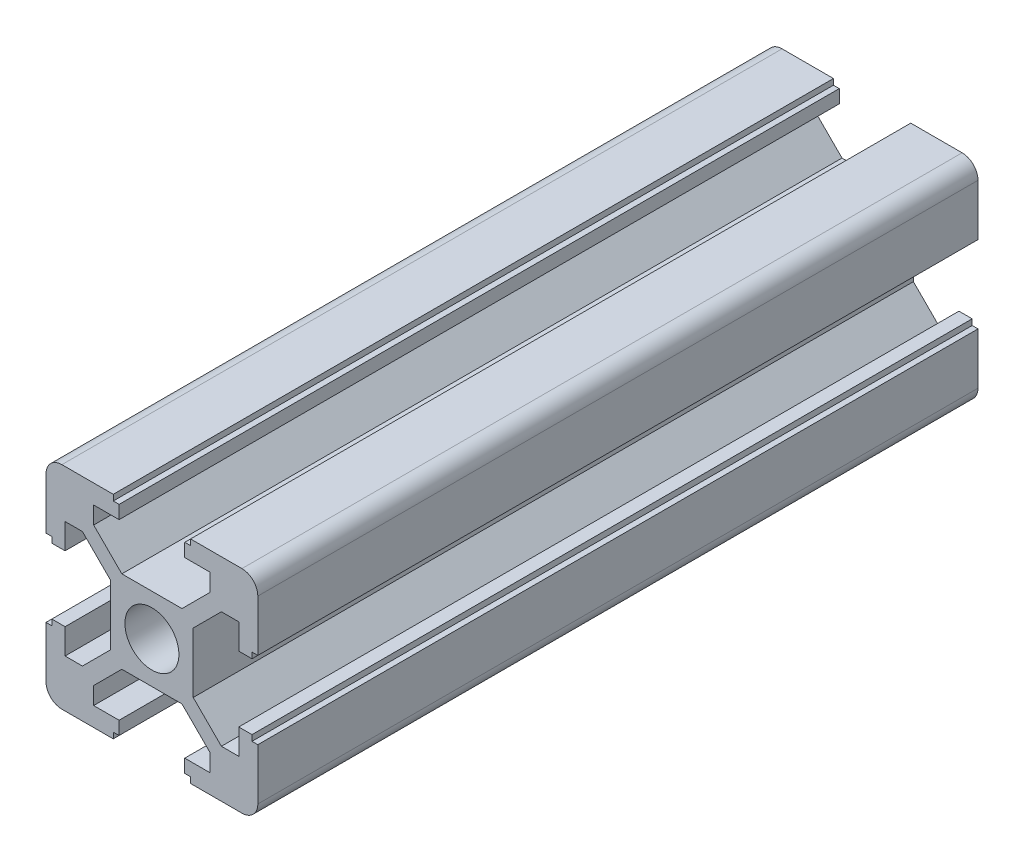
SolidWorks part; units mm, degrees
material "6063-T5"
ref_plane "前视基准面" through (0, 0, 0) normal (0, 0, 1) x (1, 0, 0)
ref_plane "上视基准面" through (0, 0, 0) normal (0, 1, 0) x (1, 0, 0)
ref_plane "右视基准面" through (0, 0, 0) normal (1, 0, 0) x (0, 0, -1)
sketch "草图1" plane through (0, 0, 0) normal (0, 0, 1) x (1, 0, 0)
  line L0 (-3.9, 2.8393) -> (-6.5607, 5.5)
  line L1 (-2.8393, 3.9) -> (2.8393, 3.9)
  line L2 (-3.9, 2.8393) -> (-3.9, -2.8393)
  line L3 (-2.8393, -3.9) -> (2.8393, -3.9)
  line L4 (3.9, 2.8393) -> (3.9, -2.8393)
  line L5 (-3.9, 3.9) -> (3.9, -3.9) construction
  line L6 (-3.9, -3.9) -> (3.9, 3.9) construction
  line L7 (-2.8393, 3.9) -> (-5.5, 6.5607)
  line L8 (-5.5, 6.5607) -> (-5.5, 8.2)
  line L9 (-5.5, 8.2) -> (-3.1, 8.2)
  line L10 (-3.1, 8.2) -> (-3.1, 9.45)
  line L11 (-3.1, 9.45) -> (-3.65, 9.45)
  line L12 (-3.65, 9.45) -> (-3.65, 10)
  line L13 (-3.65, 10) -> (-8.5, 10)
  line L14 (-6.5607, 5.5) -> (-8.2, 5.5)
  line L15 (-10, 3.65) -> (-10, 8.5)
  line L16 (-9.45, 3.65) -> (-10, 3.65)
  line L17 (-9.45, 3.1) -> (-9.45, 3.65)
  line L18 (-8.2, 3.1) -> (-9.45, 3.1)
  line L19 (-8.2, 5.5) -> (-8.2, 3.1)
  line L20 (2.8393, 3.9) -> (5.5, 6.5607)
  line L21 (3.9, 2.8393) -> (6.5607, 5.5)
  line L22 (6.5607, 5.5) -> (8.2, 5.5)
  line L23 (8.2, 5.5) -> (8.2, 3.1)
  line L24 (8.2, 3.1) -> (9.45, 3.1)
  line L25 (9.45, 3.1) -> (9.45, 3.65)
  line L26 (9.45, 3.65) -> (10, 3.65)
  line L27 (10, 3.65) -> (10, 8.5)
  line L28 (5.5, 6.5607) -> (5.5, 8.2)
  line L29 (3.65, 10) -> (8.5, 10)
  line L30 (3.65, 9.45) -> (3.65, 10)
  line L31 (3.1, 9.45) -> (3.65, 9.45)
  line L32 (3.1, 8.2) -> (3.1, 9.45)
  line L33 (5.5, 8.2) -> (3.1, 8.2)
  line L34 (3.9, -2.8393) -> (6.5607, -5.5)
  line L35 (2.8393, -3.9) -> (5.5, -6.5607)
  line L36 (5.5, -6.5607) -> (5.5, -8.2)
  line L37 (5.5, -8.2) -> (3.1, -8.2)
  line L38 (3.1, -8.2) -> (3.1, -9.45)
  line L39 (3.1, -9.45) -> (3.65, -9.45)
  line L40 (3.65, -9.45) -> (3.65, -10)
  line L41 (3.65, -10) -> (8.5, -10)
  line L42 (6.5607, -5.5) -> (8.2, -5.5)
  line L43 (10, -3.65) -> (10, -8.5)
  line L44 (9.45, -3.65) -> (10, -3.65)
  line L45 (9.45, -3.1) -> (9.45, -3.65)
  line L46 (8.2, -3.1) -> (9.45, -3.1)
  line L47 (8.2, -5.5) -> (8.2, -3.1)
  line L48 (-2.8393, -3.9) -> (-5.5, -6.5607)
  line L49 (-3.9, -2.8393) -> (-6.5607, -5.5)
  line L50 (-6.5607, -5.5) -> (-8.2, -5.5)
  line L51 (-8.2, -5.5) -> (-8.2, -3.1)
  line L52 (-8.2, -3.1) -> (-9.45, -3.1)
  line L53 (-9.45, -3.1) -> (-9.45, -3.65)
  line L54 (-9.45, -3.65) -> (-10, -3.65)
  line L55 (-10, -3.65) -> (-10, -8.5)
  line L56 (-5.5, -6.5607) -> (-5.5, -8.2)
  line L57 (-3.65, -10) -> (-8.5, -10)
  line L58 (-3.65, -9.45) -> (-3.65, -10)
  line L59 (-3.1, -9.45) -> (-3.65, -9.45)
  line L60 (-3.1, -8.2) -> (-3.1, -9.45)
  line L61 (-5.5, -8.2) -> (-3.1, -8.2)
  circle A0 centre (0, 0) radius 2.55
  arc A1 (-8.5, 10) -> (-10, 8.5) centre (-8.5, 8.5) ccw
  arc A2 (10, 8.5) -> (8.5, 10) centre (8.5, 8.5) ccw
  arc A3 (8.5, -10) -> (10, -8.5) centre (8.5, -8.5) ccw
  arc A4 (-10, -8.5) -> (-8.5, -10) centre (-8.5, -8.5) ccw
  point P74 (0, 0)
  dimension "D1" = 5.1
  dimension "D8" = 1.5
  dimension "D2" = 7.8
  dimension "D3" = 1.5
  dimension "D4" = 3.1
  dimension "D5" = 0.55
  dimension "D6" = 1.8
  dimension "D7" = 5.5
  dimension "D9" = 3.9
extrude "凸台-拉伸1" add sketch "草图1" along normal blind 68
